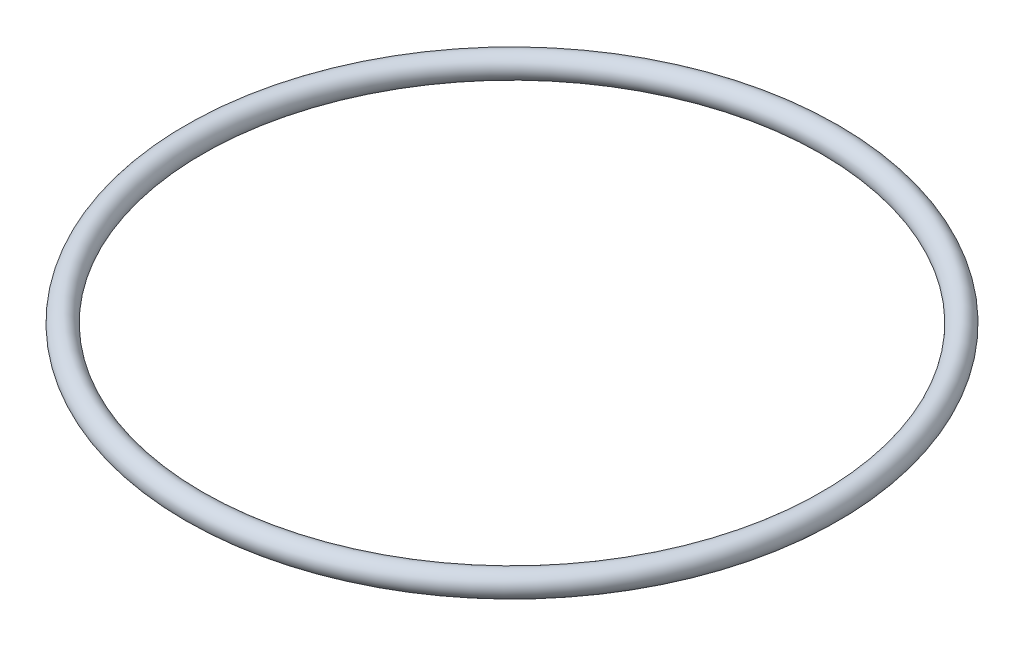
SolidWorks part; units mm, degrees
ref_plane "Front Plane" through (0, 0, 0) normal (0, 0, 1) x (1, 0, 0)
ref_plane "Top Plane" through (0, 0, 0) normal (0, 1, 0) x (1, 0, 0)
ref_plane "Right Plane" through (0, 0, 0) normal (1, 0, 0) x (0, 0, -1)
sketch "Sketch1" plane through (0, 0, 0) normal (0, 0, 1) x (1, 0, 0)
  line L0 (0, 0) -> (0, 6.1111) construction
  circle A0 centre (13.5, 0) radius 0.5
  point P5 (0.1014, 0)
  point P6 (0.1014, 0)
  point P7 (8.5417, -2.5278)
  point P8 (8.0139, -0.0833)
  dimension "D1" = 1
  dimension "D2" = 0
  dimension "D3" = 13.5
revolve "Revolve1" add sketch "Sketch1" angle 360 about L0
sketch "Sketch2" plane through (0, 0, 0) normal (0, 1, 0) x (1, 0, 0)
  circle A0 centre (0, 0) radius 13
  dimension "D1" = 26
